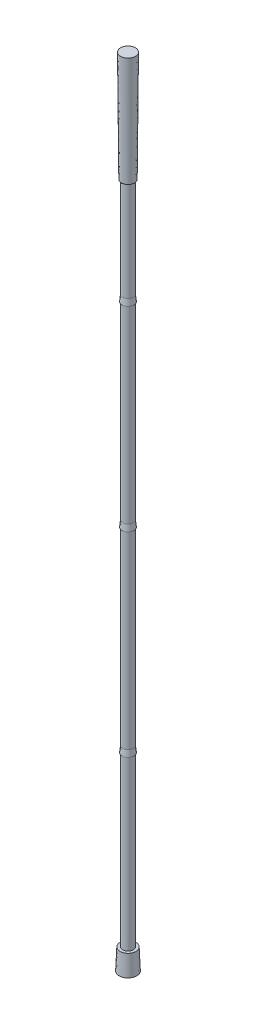
SolidWorks part; units mm, degrees
ref_plane "Front Plane" through (0, 0, 0) normal (0, 0, 1) x (1, 0, 0)
ref_plane "Top Plane" through (0, 0, 0) normal (0, 1, 0) x (1, 0, 0)
ref_plane "Right Plane" through (0, 0, 0) normal (1, 0, 0) x (0, 0, -1)
sketch "Sketch1" plane through (0, 0, 0) normal (0, 0, 1) x (1, 0, 0)
  line L8 (0, 0) -> (11.3549, 0)
  line L9 (0, 0) -> (0, -168.275)
  line L11 (0, -168.275) -> (9.9471, -168.275)
  line L12 (9.9471, -168.275) -> (11.3549, 0)
  dimension "D1" = 168.275
  dimension "D2" = 11.3549
  dimension "D3" = 9.9471
  dimension "D4" = 168.275
sketch "Sketch3" plane through (0, 0, 0) normal (0, 0, 1) x (1, 0, 0)
  line L0 (0, -1184.275) -> (0, -1216.025)
  line L2 (0, -1216.025) -> (13.3985, -1216.025)
  line L3 (0, -1184.275) -> (12.084, -1184.275)
  line L4 (12.084, -1184.275) -> (13.3985, -1216.025)
  dimension "D1" = 31.75
  dimension "D2" = 13.3985
  dimension "D3" = 12.084
  dimension "D4" = 31.75
revolve "Revolve1" add sketch "Sketch3" angle 360 about L0
revolve "Revolve3" add sketch "Sketch1" angle 360 about L9
sketch "Sketch8" plane through (0, 0, 0) normal (0, 0, 1) x (1, 0, 0)
  line L0 (0, -168.275) -> (0, -320.675)
  line L1 (0, -168.275) -> (8.0709, -168.275)
  line L2 (0, -168.275) -> (9.9471, -168.275) construction
  line L5 (8.0709, -168.275) -> (8.0709, -320.675)
  line L6 (0, -320.675) -> (0, -330.2)
  line L7 (0, -330.2) -> (9.144, -330.2)
  line L8 (9.144, -330.2) -> (8.0709, -320.675)
  dimension "D1" = 152.4
  dimension "D2" = 8.0709
  dimension "D3" = 9.525
  dimension "D4" = 9.144
revolve "Revolve4" add sketch "Sketch8" angle 360 about L0
sketch "Sketch11" plane through (0, 0, 0) normal (0, 0, 1) x (1, 0, 0)
  line L0 (0, -330.2) -> (0, -619.125)
  line L1 (-9.144, -330.2) -> (9.144, -330.2) construction
  line L2 (0, -330.2) -> (8.0645, -330.2)
  line L3 (8.0645, -330.2) -> (8.0645, -619.125)
  line L4 (0, -619.125) -> (0, -628.65)
  line L5 (0, -628.65) -> (9.144, -628.65)
  line L6 (8.0645, -619.125) -> (9.144, -628.65)
  dimension "D1" = 288.925
  dimension "D2" = 8.0645
  dimension "D3" = 9.525
  dimension "D4" = 9.144
  dimension "D5" = 288.925
revolve "Revolve5" add sketch "Sketch11" angle 360 about L0
sketch "Sketch13" plane through (0, 0, 0) normal (0, 0, 1) x (1, 0, 0)
  line L0 (0, -628.65) -> (8.0454, -628.65)
  line L1 (-9.144, -628.65) -> (9.144, -628.65) construction
  line L2 (0, -628.65) -> (0, -927.1)
  line L3 (8.0454, -628.65) -> (8.0455, -917.575)
  line L4 (0, -927.1) -> (9.144, -927.1)
  line L5 (9.144, -927.1) -> (8.0455, -917.575)
  dimension "D1" = 8.0454
  dimension "D2" = 298.45
  dimension "D3" = 288.925
  dimension "D4" = 9.144
revolve "Revolve6" add sketch "Sketch13" angle 360 about L2
sketch "Sketch14" plane through (0, 0, 0) normal (0, 0, 1) x (1, 0, 0)
  line L0 (-9.144, -927.1) -> (9.144, -927.1) construction
  line L1 (0, -927.1) -> (8.1026, -927.1)
  line L2 (0, -927.1) -> (0, -1184.275)
  line L3 (0, -1184.275) -> (8.1026, -1184.275)
  line L4 (8.1026, -927.1) -> (8.1026, -1184.275)
  dimension "D1" = 257.175
  dimension "D2" = 8.1026
revolve "Revolve7" add sketch "Sketch14" angle 360 about L2
